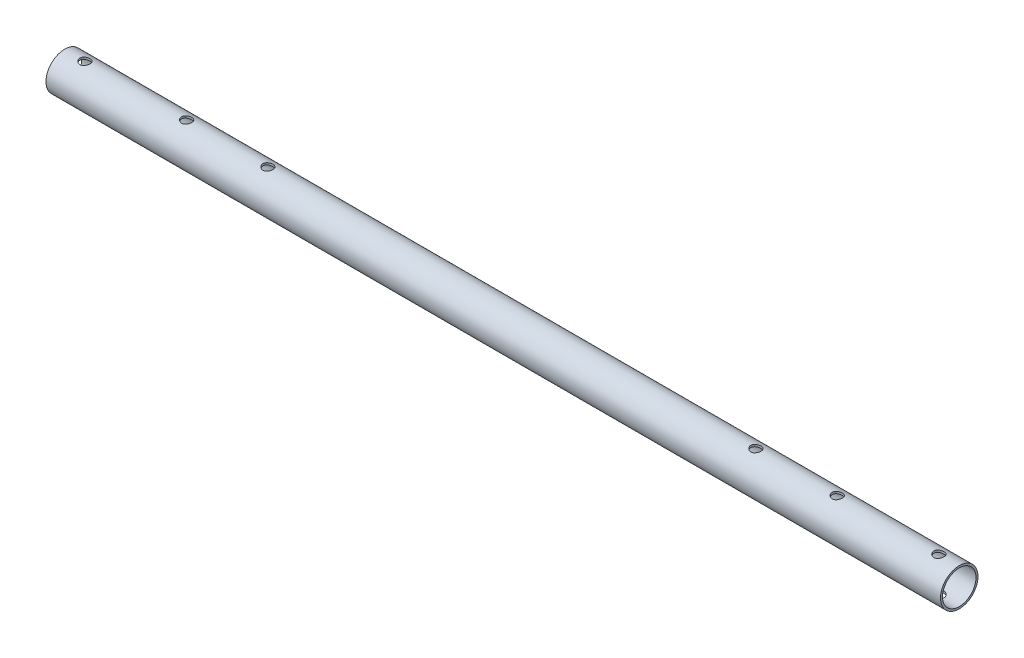
SolidWorks part; units mm, degrees
material "Galvanized Steel"
ref_plane "Front Plane" through (0, 0, 0) normal (0, 0, 1) x (1, 0, 0)
ref_plane "Top Plane" through (0, 0, 0) normal (0, 1, 0) x (1, 0, 0)
ref_plane "Right Plane" through (0, 0, 0) normal (1, 0, 0) x (0, 0, -1)
sketch "Sketch3" plane through (0, 0, 0) normal (1, 0, 0) x (0, 0, -1)
  circle A0 centre (0, 0) radius 10.4648
  circle A1 centre (0, 0) radius 11.7094
  dimension "D1" = 20.9296
  dimension "D2" = 23.4188
extrude "Boss-Extrude1" add sketch "Sketch3" along normal blind 558.8
sketch "Sketch4" plane through (0, 0, 0) normal (0, 1, 0) x (1, 0, 0)
  line L0 (558.8, -11.7094) -> (558.8, 11.7094) construction
  line L1 (0, 11.7094) -> (0, -11.7094) construction
  circle A0 centre (431.8, 0) radius 3.175
  circle A1 centre (12.7, 0) radius 3.175
  circle A2 centre (76.2, 0) radius 3.175
  circle A3 centre (482.6, 0) radius 3.175
  circle A4 centre (546.1, 0) radius 3.175
  circle A5 centre (127, 0) radius 3.175
  dimension "D1" = 6.35
  dimension "D2" = 6.35
  dimension "D3" = 50.8
  dimension "D4" = 6.35
  dimension "D5" = 6.35
  dimension "D6" = 50.8
  dimension "D7" = 12.7
  dimension "D8" = 12.7
  dimension "D9" = 63.5
  dimension "D10" = 63.5
extrude "Cut-Extrude1" cut sketch "Sketch4" along normal through all and the other way through all
